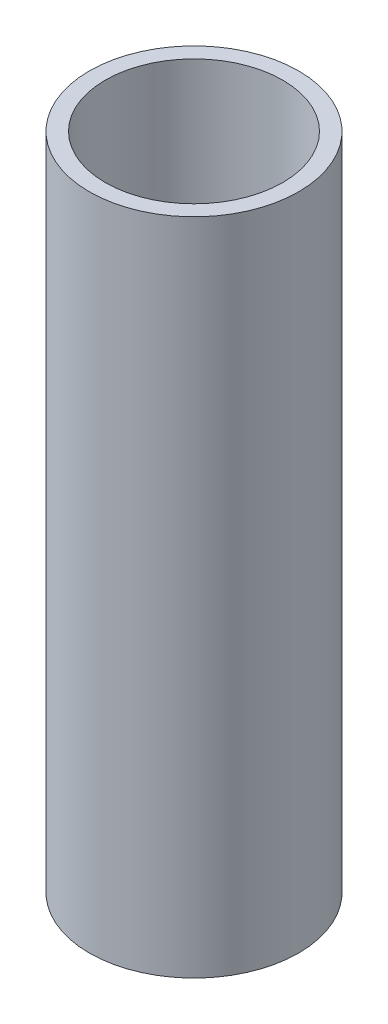
SolidWorks part; units mm, degrees
ref_plane "Front Plane" through (0, 0, 0) normal (0, 0, 1) x (1, 0, 0)
ref_plane "Top Plane" through (0, 0, 0) normal (0, 1, 0) x (1, 0, 0)
ref_plane "Right Plane" through (0, 0, 0) normal (1, 0, 0) x (0, 0, -1)
sketch "Sketch1" plane through (0, 0, 0) normal (0, 1, 0) x (1, 0, 0)
  circle A0 centre (0, 0) radius 15.875
  circle A1 centre (0, 0) radius 13.462
  dimension "D1" = 31.75
  dimension "D2" = 2.413
extrude "Boss-Extrude1" add sketch "Sketch1" along normal blind 100
